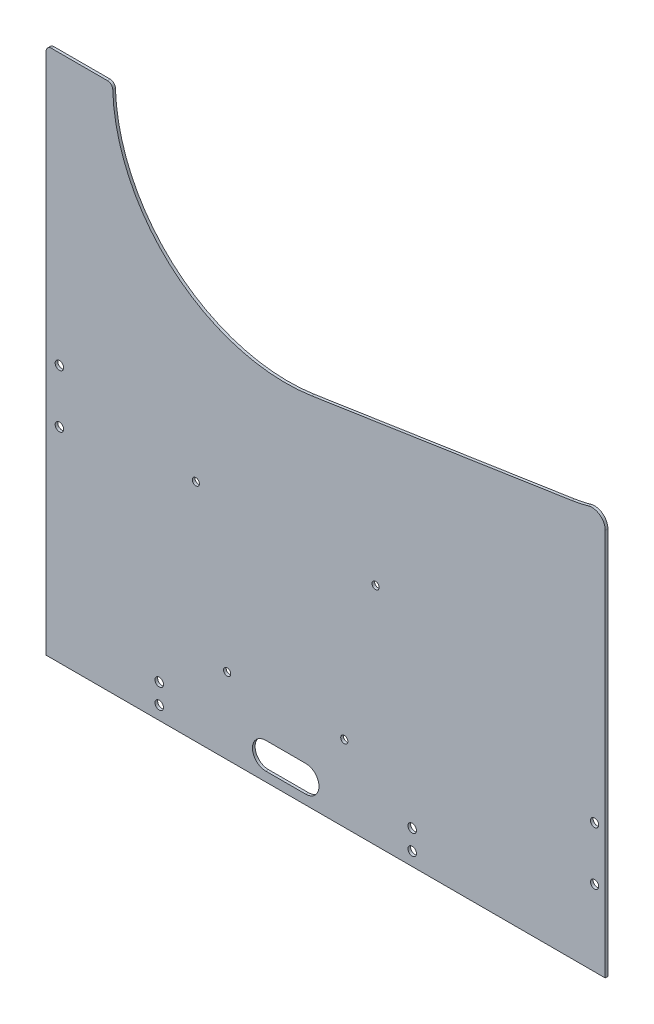
SolidWorks part; units mm, degrees
material "Thornel Mat VMA"
ref_plane "前视基准面" through (0, 0, 0) normal (0, 0, 1) x (1, 0, 0)
ref_plane "上视基准面" through (0, 0, 0) normal (0, 1, 0) x (1, 0, 0)
ref_plane "右视基准面" through (0, 0, 0) normal (1, 0, 0) x (0, 0, -1)
sketch "草图1" plane through (0, 0, 0) normal (0, 0, 1) x (1, 0, 0)
  line L1 (-105, -116.5) -> (105, -116.5)
  line L2 (-105, -116.5) -> (-105, 116.5)
  line L3 (-105, 116.5) -> (105, 116.5)
  line L4 (105, -116.5) -> (105, 116.5)
  line L5 (-105, -116.5) -> (105, 116.5) construction
  line L6 (-105, 116.5) -> (105, -116.5) construction
  point P0 (0, 0)
  dimension "D1" = 233
  dimension "D2" = 210
extrude "凸台-拉伸1" add sketch "草图1" along normal blind 1
sketch "草图2" plane through (0, 0, 1) normal (0, 0, 1) x (1, 0, 0)
  line L0 (-15, 100.25) -> (-15, 0) construction
  line L1 (-15, 0) -> (0, 0) construction
  circle A2 centre (-15, 100.25) radius 65
  dimension "D1" = 130
  dimension "D2" = 15
  dimension "D3" = 100.25
extrude "切除-拉伸1" cut sketch "草图2" against normal blind 2
sketch "草图3" plane through (0, 0, 1) normal (0, 0, 1) x (1, 0, 0)
  line L0 (-15, 100.25) -> (105, 100.25) construction
  line L1 (105, -116.5) -> (105, 116.5) construction
  line L2 (-105, 100.25) -> (105, 100.25)
  line L3 (-105, 116.5) -> (-105, -116.5) construction
  line L4 (-105, 100.25) -> (-105, 116.5)
  line L5 (-105, 116.5) -> (105, 116.5)
  line L6 (105, 116.5) -> (105, 100.25)
extrude "切除-拉伸2" cut sketch "草图3" against normal blind 2
sketch "草图4" plane through (0, 0, 1) normal (0, 0, 1) x (1, 0, 0)
  line L0 (-105, 100.15) -> (105, 100.15)
  line L1 (-105, 100.25) -> (-105, -116.5) construction
  line L2 (105, -116.5) -> (105, 100.25) construction
  line L3 (-105, 100.15) -> (-105, 100.25)
  line L4 (-105, 100.25) -> (105, 100.25)
  line L5 (105, 100.25) -> (105, 100.15)
  dimension "D1" = 0.1
extrude "切除-拉伸3" cut sketch "草图4" against normal blind 2
sketch "草图5" plane through (0, 0, 1) normal (0, 0, 1) x (1, 0, 0)
  line L0 (-15, 100.25) -> (85, 100.25) construction
  line L1 (4.5, 38.244) -> (95.5, 66.8621)
  line L2 (49.9999, 100.15) -> (50, 100.274)
  arc A0 (4.5, 38.244) -> (49.9999, 100.15) centre (-15, 100.25) ccw
  arc A1 (95.5, 66.8621) -> (50, 100.274) centre (85, 100.25) ccw
  arc A2 (-79.9999, 100.15) -> (49.9999, 100.15) centre (-15, 100.25) ccw construction
  dimension "D2" = 70
  dimension "D1" = 100
extrude "切除-拉伸4" cut sketch "草图5" against normal blind 2
sketch "草图6" plane through (0, 0, 1) normal (0, 0, 1) x (1, 0, 0)
  line L0 (105, 50.25) -> (135, 90.25)
  line L1 (105, -116.5) -> (105, 71.5272) construction
  line L2 (135, 90.25) -> (135, 100.25)
  line L3 (85, 100.25) -> (135, 100.25) construction
  line L4 (120, 100.25) -> (135, 100.25)
  line L5 (105, 71.5272) -> (105, 50.25)
  arc A0 (105, 71.5272) -> (120, 100.25) centre (85, 100.25) ccw
  dimension "D2" = 50
  dimension "D3" = 50
  dimension "D4" = 10
extrude "凸台-拉伸2" [suppressed] add sketch "草图6" against normal up to surface (1 mm away)
sketch "草图7" [suppressed] plane through (0, 0, 1) normal (0, 0, 1) x (1, 0, 0)
  line L2 (35, -51) -> (105, -51) construction
  line L3 (105, -116.5) -> (105, 71.5272) construction
  line L4 (35, -84) -> (105, -84)
  line L5 (35, -84) -> (35, -18)
  line L6 (35, -18) -> (105, -18)
  line L7 (105, -84) -> (105, -18)
  line L8 (35, -84) -> (105, -18) construction
  line L9 (35, -18) -> (105, -84) construction
  point P0 (70, -51)
  dimension "D1" = 70
  dimension "D2" = 51
  dimension "D3" = 66
extrude "切除-拉伸5" [suppressed] cut sketch "草图7" against normal blind 2
sketch "草图8" plane through (0, 0, 1) normal (0, 0, 1) x (1, 0, 0)
  line L0 (0, 0) -> (-100, 0) construction
  line L1 (-100, 0) -> (-100, -1.5) construction
  line L2 (-100, -1.5) -> (-100, -21.5) construction
  circle A2 centre (-100, -21.5) radius 1.6
  circle A3 centre (-100, -1.5) radius 1.6
  dimension "D4" = 3.2
  dimension "D1" = 100
  dimension "D2" = 1.5
  dimension "D3" = 20
extrude "切除-拉伸6" cut sketch "草图8" against normal blind 1
sketch "草图9" [suppressed] plane through (0, 0, 1) normal (0, 0, 1) x (1, 0, 0)
  circle A0 centre (97.8, -101.2728) radius 2 construction
  circle A1 centre (97.8, -85.2728) radius 2 construction
  circle A2 centre (97.8, -101.2728) radius 2
  circle A3 centre (97.8, -85.2728) radius 2
extrude "切除-拉伸7" [suppressed] cut sketch "草图9" against normal blind 10.6
sketch "草图11" [suppressed] plane through (0, 0, 1) normal (0, 0, 1) x (1, 0, 0)
  line L1 (103.4, -86.7228) -> (103.4, -111.7228)
  line L3 (35, -84) -> (96.2573, -84) construction
  dimension "D1" = 103.4
  dimension "D2" = 25
  dimension "D3" = 2.7228
sketch "草图10" [suppressed] plane through (0, 0, 1) normal (0, 0, 1) x (1, 0, 0)
  line L0 (105, -116.5) -> (105, -84) construction
  line L1 (103.3, -112.7228) -> (106.7, -112.7228)
  line L2 (103.3, -112.7228) -> (103.3, -85.7228)
  line L3 (103.3, -85.7228) -> (106.7, -85.7228)
  line L4 (106.7, -112.7228) -> (106.7, -85.7228)
  line L5 (103.3, -112.7228) -> (106.7, -85.7228) construction
  line L6 (103.3, -85.7228) -> (106.7, -112.7228) construction
  line L8 (103.4, -86.7228) -> (103.4, -111.7228) construction
  line L9 (103.4, -99.2228) -> (105, -99.2228) construction
  point P0 (105, -99.2228)
  dimension "D2" = 27
  dimension "D3" = 1.7
extrude "切除-拉伸8" [suppressed] cut sketch "草图10" against normal blind 10.6
sketch "草图12" plane through (0, 0, 0) normal (0, 0, -1) x (-1, 0, 0)
  line L0 (0, 0) -> (0, -13.7) construction
  line L1 (0, -13.7) -> (-18.75, -13.7) construction
  line L2 (0, -13.7) -> (48.75, -13.7) construction
  line L3 (-7, -69.7) -> (0, -69.7) construction
  line L4 (0, -69.7) -> (0, -13.7) construction
  line L5 (0, -69.7) -> (37, -69.7) construction
  circle A8 centre (-18.75, -13.7) radius 1.35
  circle A9 centre (48.75, -13.7) radius 1.35
  circle A10 centre (-7, -69.7) radius 1.35
  circle A11 centre (37, -69.7) radius 1.35
  dimension "D1" = 13.7
  dimension "D7" = 2.7
  dimension "D2" = 18.75
  dimension "D3" = 48.75
  dimension "D4" = 56
  dimension "D5" = 7
  dimension "D6" = 37
extrude "切除-拉伸9" cut sketch "草图12" against normal blind 10
sketch "草图13" plane through (0, 0, 0) normal (0, 0, -1) x (-1, 0, 0)
  line L0 (7.5, -89.7) -> (22.5, -89.7) construction
  line L1 (7.5, -84.7) -> (22.5, -84.7)
  line L2 (7.5, -94.7) -> (22.5, -94.7)
  line L3 (-7, -69.7) -> (37, -69.7) construction
  line L4 (15, -69.7) -> (15, -89.7) construction
  arc A0 (7.5, -84.7) -> (7.5, -94.7) centre (7.5, -89.7) ccw
  arc A1 (22.5, -94.7) -> (22.5, -84.7) centre (22.5, -89.7) ccw
  point P2 (15, -89.7)
  dimension "D1" = 5
  dimension "D2" = 15
  dimension "D3" = 20
extrude "切除-拉伸10" cut sketch "草图13" against normal blind 10
fillet "圆角1" [suppressed] radius 0.8
fillet "圆角2" [suppressed] radius 2
fillet "圆角3" radius 2 5 edges at (-105, 100.15, 0.5) (-105, -116.5, 0.5) (-79.9999, 100.15, 0.5) (105, 71.5272, 0.5) (105, -116.5, 0.5)
sketch "草图14" [suppressed] plane through (0, 0, 1) normal (0, 0, 1) x (1, 0, 0)
  line L0 (-62.5, -103.75) -> (-62.5, -111.25) construction
  line L1 (-62.5, -103.75) -> (0, -103.75) construction
  line L2 (0, -103.75) -> (0, 0) construction
  line L3 (0, -103.75) -> (32.5, -103.75) construction
  line L4 (32.5, -103.75) -> (32.5, -112.5) construction
  circle A4 centre (-62.5, -111.25) radius 1.6
  circle A5 centre (-62.5, -103.75) radius 1.6
  circle A7 centre (32.5, -103.75) radius 1.6
  circle A8 centre (32.5, -112.5) radius 1.6
  dimension "D6" = 3.2
  dimension "D1" = 103.75
  dimension "D2" = 62.5
  dimension "D3" = 7.5
  dimension "D4" = 32.5
  dimension "D5" = 8.75
sketch "草图15" plane through (0, 0, 0) normal (0, 0, -1) x (-1, 0, 0)
  line L0 (0, 0) -> (0, -85.75) construction
  line L1 (0, -85.75) -> (-32.5, -85.75) construction
  line L2 (-32.5, -85.75) -> (-32.5, -93.25) construction
  line L3 (0, -85.75) -> (62.5, -85.75) construction
  line L4 (62.5, -85.75) -> (62.5, -93.25) construction
  circle A4 centre (-32.5, -85.75) radius 1.6
  circle A5 centre (-32.5, -93.25) radius 1.6
  circle A6 centre (62.5, -85.75) radius 1.6
  circle A7 centre (62.5, -93.25) radius 1.6
  dimension "D6" = 3.2
  dimension "D1" = 85.75
  dimension "D2" = 32.5
  dimension "D3" = 7.5
  dimension "D4" = 62.5
  dimension "D5" = 7.5
extrude "切除-拉伸11" [suppressed] cut sketch "草图14" against normal blind 10
extrude "切除-拉伸12" cut sketch "草图15" against normal blind 10
sketch "草图16" [suppressed] plane through (0, 0, 1) normal (0, 0, 1) x (1, 0, 0)
  line L0 (37, -84) -> (96.2573, -84) construction
  line L1 (87, -84) -> (105, -84)
  line L2 (87, -84) -> (87, -81)
  line L3 (87, -81) -> (105, -81)
  line L4 (105, -84) -> (105, -81)
  line L5 (105, -84.9228) -> (105, -84) construction
  dimension "D1" = 3
  dimension "D2" = 18
extrude "凸台-拉伸3" [suppressed] add sketch "草图16" against normal up to surface (1 mm away)
fillet "圆角4" [suppressed] radius 1.5
fillet "圆角5" [suppressed] radius 1.5
sketch "草图17" plane through (0, 0, 0) normal (0, 0, -1) x (-1, 0, 0)
  line L0 (0, 0) -> (0, -49.75) construction
  line L1 (0, -49.75) -> (-101, -49.75) construction
  line L2 (-101, -49.75) -> (-101, -69.75) construction
  circle A2 centre (-101, -49.75) radius 1.55
  circle A3 centre (-101, -69.75) radius 1.55
  dimension "D4" = 3.1
  dimension "D1" = 49.75
  dimension "D2" = 101
  dimension "D3" = 20
extrude "切除-拉伸13" cut sketch "草图17" against normal blind 10
sketch "草图18" plane through (0, 0, 0) normal (0, 0, -1) x (-1, 0, 0)
  line L0 (-85, 100.25) -> (15, 100.25) construction
  line L1 (-92.5, 50.8157) -> (5.25, 35.9854)
  line L2 (-105, 54.4242) -> (-105, 79.4242)
  line L3 (-105, -114.5) -> (-105, 67.9235) construction
  line L4 (-105, 79.4242) -> (5.25, 35.9854)
  arc A0 (-105, 54.4242) -> (-92.5, 50.8157) centre (-85, 100.25) ccw
  arc A2 (-4.5, 38.244) -> (79.9681, 98.2127) centre (15, 100.25) ccw construction
  dimension "D1" = 100
  dimension "D2" = 25
extrude "切除-拉伸14" cut sketch "草图18" against normal blind 10
fillet "圆角6" radius 5 1 edges at (105, 54.4242, 0.5)
sketch "草图19" [suppressed] plane through (0, 0, 1) normal (0, 0, 1) x (1, 0, 0)
  line L0 (103, -18) -> (37, -18) construction
  line L1 (105, -16) -> (105, 47.335) construction
  circle A0 centre (55, -18) radius 5
  dimension "D2" = 10
  dimension "D1" = 50
extrude "切除-拉伸15" [suppressed] cut sketch "草图19" against normal blind 10
fillet "圆角7" [suppressed] radius 5
sketch "草图20" [suppressed] plane through (0, 0, 1) normal (0, 0, 1) x (1, 0, 0)
  line L0 (87, -82.5) -> (87, -73)
  line L1 (87, -73) -> (105, -73)
  line L2 (105, -73) -> (105, -81)
  line L3 (105, -81) -> (87, -82.5)
  line L4 (105, -81) -> (88.5, -81) construction
  dimension "D1" = 8
extrude "凸台-拉伸4" [suppressed] add sketch "草图20" against normal up to surface (1 mm away)
sketch "草图21" [suppressed] plane through (0, 0, 1) normal (0, 0, 1) x (1, 0, 0)
  line L0 (77, -84) -> (77, -73)
  line L1 (37, -84) -> (85.5, -84) construction
  line L2 (77, -73) -> (87, -73)
  line L3 (87, -73) -> (87, -82.5) construction
  line L4 (77, -84) -> (87, -84)
  line L5 (87, -84) -> (87, -73)
  dimension "D1" = 10
extrude "凸台-拉伸5" [suppressed] add sketch "草图21" against normal up to surface (1 mm away)
sketch "草图22" [suppressed] plane through (0, 0, 1) normal (0, 0, 1) x (1, 0, 0)
  circle A0 centre (97.8, -85.2728) radius 2
  arc A1 (96.2573, -84) -> (99.3427, -84) centre (97.8, -85.2728) ccw construction
extrude "切除-拉伸16" [suppressed] cut sketch "草图22" against normal blind 10
fillet "圆角8" [suppressed] radius 5
fillet "圆角9" [suppressed] radius 2
sketch "草图23" [suppressed] plane through (0, 0, 1) normal (0, 0, 1) x (1, 0, 0)
  circle A0 centre (101, -10) radius 1.25 construction
  circle A1 centre (101, -10) radius 1.25 construction
  circle A2 centre (101, -10) radius 1.6
  dimension "D1" = 3.2
extrude "切除-拉伸17" [suppressed] cut sketch "草图23" against normal blind 10
sketch "草图24" plane through (0, 0, 1) normal (0, 0, 1) x (1, 0, 0)
  line L0 (-105, 98.15) -> (-105, -114.5) construction
  line L1 (-105, -98.25) -> (105, -98.25)
  line L2 (-105, -98.25) -> (-105, -116.5)
  line L3 (-105, -116.5) -> (105, -116.5)
  line L4 (105, -98.25) -> (105, -116.5)
  line L5 (105, -114.5) -> (105, 47.335) construction
  line L6 (-103, -116.5) -> (103, -116.5) construction
  circle A0 centre (32.5, -93.25) radius 1.6 construction
  dimension "D1" = 5
extrude "切除-拉伸18" cut sketch "草图24" against normal blind 10
